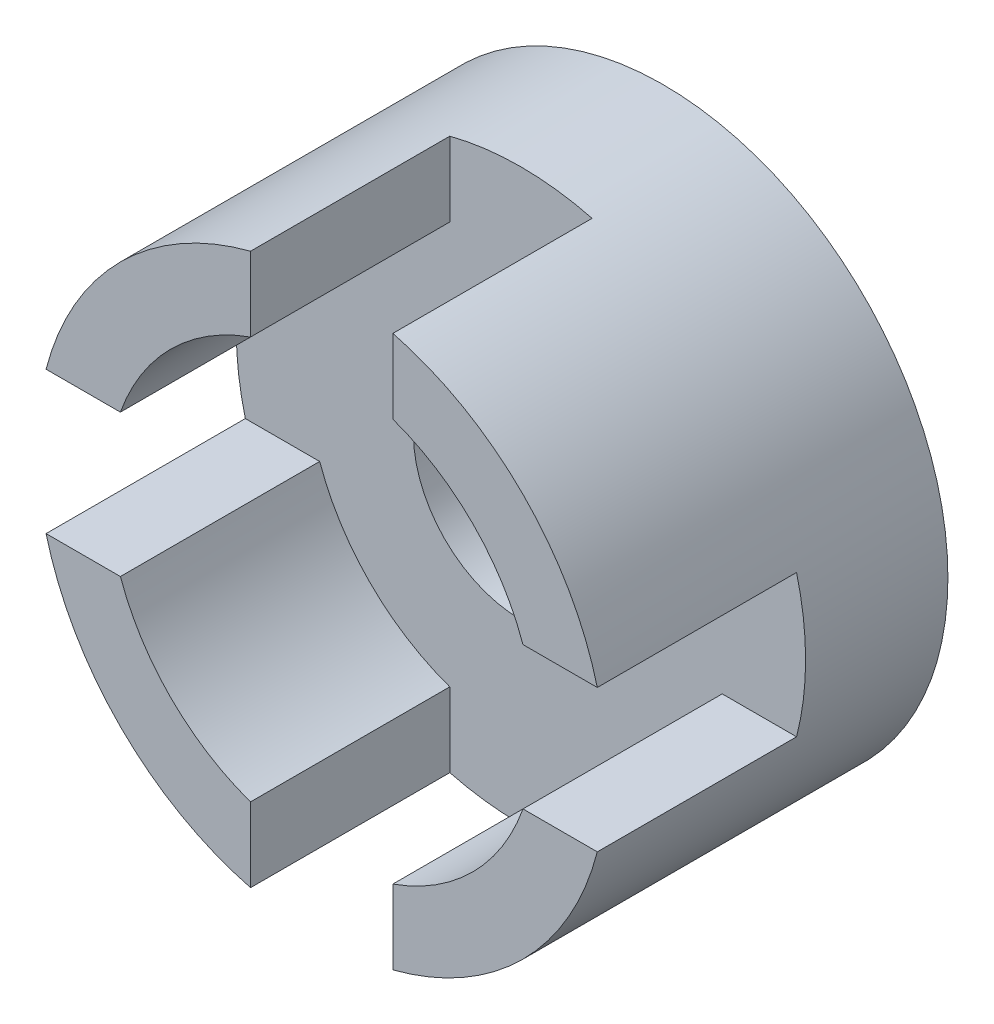
SolidWorks part; units mm, degrees
material "Custom Plastic"
ref_plane "X-Y Datum" through (0, 0, 0) normal (0, 0, 1) x (1, 0, 0)
ref_plane "X-Z Datum" through (0, 0, 0) normal (0, 1, 0) x (1, 0, 0)
ref_plane "Y-Z Datum" through (0, 0, 0) normal (1, 0, 0) x (0, 0, -1)
sketch "Sketch2" plane through (0, 0, 0) normal (0, 0, 1) x (1, 0, 0)
  circle A0 centre (0, 0) radius 3.5
  circle A1 centre (0, 0) radius 6.35
  circle A2 centre (0, 0) radius 4.7625
  dimension "D1" = 7
  dimension "D2" = 12.7
  dimension "D3" = 9.525
extrude "Boss-Extrude1" add sketch "Sketch2" along normal blind 7.62 contours A2 A0 | A1 A2 | A0
sketch "Sketch3" plane through (0, 0, 7.62) normal (0, 0, 1) x (1, 0, 0)
  circle A1 centre (0, 0) radius 4.7625
  circle A2 centre (0, 0) radius 4.7625
  circle A3 centre (0, 0) radius 6.35
  circle A4 centre (0, 0) radius 6.35
  circle A5 centre (0, 0) radius 3.5
  circle A6 centre (0, 0) radius 3.5
  dimension "D1" = 0
  dimension "D2" = 0
  dimension "D3" = 0
extrude "Cut-Extrude1" cut sketch "Sketch3" against normal offset from surface (4.445 mm away) 3.175 contours A6 | A2 A6 up to face at (6.35, 0, 0)
hole_wizard "M4 Clearance Hole1" positions "Sketch4" profile "Sketch5" hole size "M4" standard "ANSI Metric" end condition through all
sketch "Sketch4" plane through (0, 0, 3.175) normal (0, 0, 1) x (1, 0, 0)
  point P0 (0, 0)
sketch "Sketch5" plane through (0, 0, 3.175) normal (1, 0, 0) x (0, -1, 0)
  line L0 (0, 0) -> (0, 3.175)
  line L1 (0, 3.175) -> (2.4, 3.175)
  line L2 (2.4, 3.175) -> (2.4, 0)
  line L5 (2.4, 0) -> (0, 0)
  line L11 (0, -6.35) -> (0, 107.95) construction
  dimension "Thru Hole Dia." = 4.8
  dimension "Thru Hole Depth" = 3.175
sketch "Sketch6" plane through (0, 0, 7.62) normal (0, 0, 1) x (1, 0, 0)
  line L0 (0, 6.35) -> (0, -6.35) construction
  line L1 (-6.35, 0) -> (6.35, 0) construction
  line L2 (-1.5875, 6.35) -> (-1.5875, -6.35)
  line L3 (1.5875, 6.35) -> (1.5875, -6.35)
  line L4 (-6.35, -1.5875) -> (6.35, -1.5875)
  line L5 (-6.35, 1.5875) -> (6.35, 1.5875)
  circle A0 centre (0, 0) radius 6.35 construction
  circle A1 centre (0, 0) radius 6.35
  point P7 (0, 0)
  point P11 (0, 0)
  circle M4 centre (0, 0) radius 4.7625
  circle M5 centre (0, 0) radius 6.35
  dimension "D1" = 1.5875
  dimension "D2" = 1.5875
  dimension "D3" = 1.5875
  dimension "D4" = 1.5875
extrude "Cut-Extrude2" cut sketch "Sketch6" against normal up to surface (4.445 mm away) contours L3 L2 M5 M4
pattern_circular "CirPattern1" count 4 over 360 about axis through (0, 0, 0) along (0, 0, 1) of "Cut-Extrude2"
